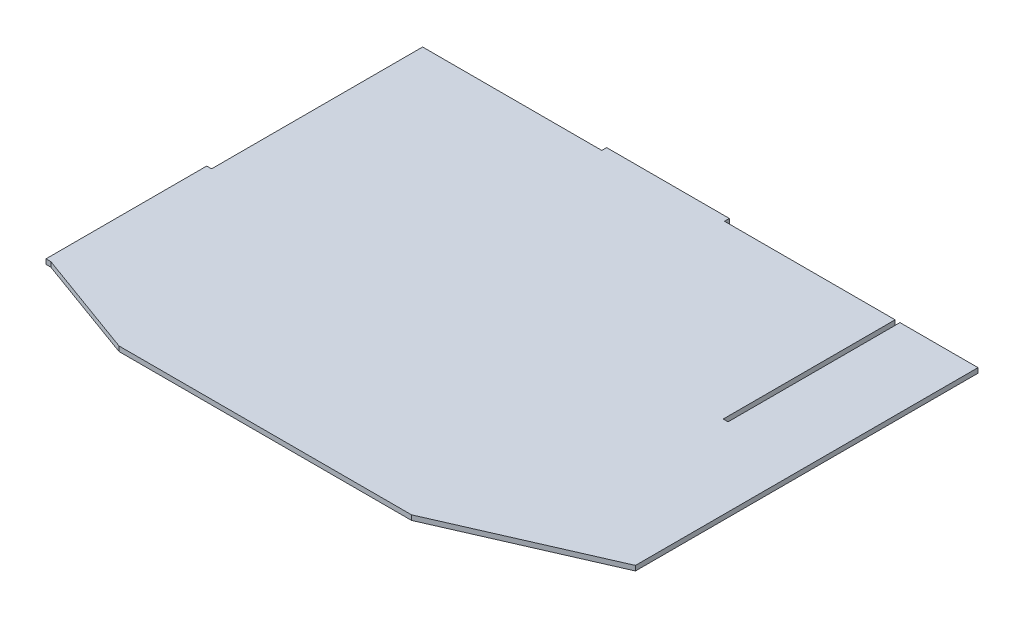
SolidWorks part; units mm, degrees
material "6061-T6 (SS)"
ref_plane "X-Y Datum" through (0, 0, 0) normal (0, 0, 1) x (1, 0, 0)
ref_plane "X-Z Datum" through (0, 0, 0) normal (0, 1, 0) x (1, 0, 0)
ref_plane "Y-Z Datum" through (0, 0, 0) normal (1, 0, 0) x (0, 0, -1)
sketch "Sketch1" plane through (0, 0, 0) normal (0, 0, 1) x (1, 0, 0)
  line L1 (-154.0561, -1.5875) -> (154.0561, -1.5875)
  line L2 (-154.0561, -1.5875) -> (-154.0561, 1.5875)
  line L3 (-154.0561, 1.5875) -> (154.0561, 1.5875)
  line L4 (154.0561, -1.5875) -> (154.0561, 1.5875)
  line L5 (-154.0561, -1.5875) -> (154.0561, 1.5875) construction
  line L6 (-154.0561, 1.5875) -> (154.0561, -1.5875) construction
  point P0 (0, 0)
  dimension "D1" = 3.175
  dimension "D2" = 308.1122
extrude "Boss-Extrude1" add sketch "Sketch1" along normal blind 267.83
sketch "Sketch3" plane through (154.0561, 0, 0) normal (1, 0, 0) x (0, 0, -1)
  line L0 (-267.83, 1.5875) -> (0, 1.5875) construction
  line L1 (-267.83, -1.5875) -> (-112.128, -1.5875)
  line L2 (-267.83, -1.5875) -> (-267.83, 1.5875)
  line L3 (-267.83, 1.5875) -> (-112.128, 1.5875)
  line L4 (-112.128, -1.5875) -> (-112.128, 1.5875)
  dimension "D1" = 155.702
extrude "Boss-Extrude3" add sketch "Sketch3" along normal blind 3.175
sketch "Sketch4" plane through (0, 0, 267.83) normal (0, 0, 1) x (1, 0, 0)
  line L1 (157.2311, -1.5875) -> (208.1047, -1.5875)
  line L2 (157.2311, -1.5875) -> (157.2311, 1.5875)
  line L3 (157.2311, 1.5875) -> (208.1047, 1.5875)
  line L4 (208.1047, -1.5875) -> (208.1047, 1.5875)
  dimension "D1" = 3.175
  dimension "D2" = 50.8737
extrude "Boss-Extrude4" add sketch "Sketch4" against normal blind 267.83
sketch "Sketch6" plane through (0, 1.5875, 0) normal (0, 1, 0) x (1, 0, 0)
  line L0 (106.5047, -267.83) -> (106.5047, -223.38)
  line L1 (208.1047, -267.83) -> (-154.0561, -267.83) construction
  line L2 (208.1047, -223.38) -> (106.5047, -223.38)
  line L3 (208.1047, 0) -> (208.1047, -267.83) construction
  line L4 (106.5047, -267.83) -> (208.1047, -223.38)
  line M9 (-154.0561, -267.83) -> (208.1047, -267.83)
  line M10 (208.1047, -267.83) -> (208.1047, 0)
  dimension "D1" = 44.45
  dimension "D2" = 101.6
extrude "Cut-Extrude1" cut sketch "Sketch6" against normal through all contours L4 M9 M10
sketch "Sketch8" plane through (0, 0, 0) normal (0, 0, -1) x (-1, 0, 0)
  line L1 (37.216, 1.5875) -> (-42.784, 1.5875)
  line L2 (37.216, 1.5875) -> (37.216, -1.5875)
  line L3 (37.216, -1.5875) -> (-42.784, -1.5875)
  line L4 (-42.784, 1.5875) -> (-42.784, -1.5875)
extrude "Boss-Extrude6" add sketch "Sketch8" along normal blind 3.175
sketch "Sketch11" plane through (0, -1.5875, 0) normal (0, -1, 0) x (1, 0, 0)
  line L0 (-84.2061, 267.83) -> (-84.2061, 242.43)
  line L1 (-154.0561, 267.83) -> (106.5047, 267.83) construction
  line L2 (-154.0561, 242.43) -> (-84.2061, 242.43)
  line L3 (-154.0561, 267.83) -> (-154.0561, 0) construction
  line L4 (-154.0561, 242.43) -> (-84.2061, 267.83)
  line M4 (-154.0561, 267.83) -> (-154.0561, 0)
  line M18 (106.5047, 267.83) -> (-154.0561, 267.83)
  dimension "D1" = 69.85
  dimension "D2" = 25.4
extrude "Cut-Extrude3" cut sketch "Sketch11" against normal through all contours L4 M4 M18
sketch "Sketch13" plane through (-154.0561, 0, 0) normal (-1, 0, 0) x (0, 0, 1)
  line L1 (137.65, -1.598) -> (242.43, -1.598)
  line L2 (137.65, -1.598) -> (137.65, 1.5875)
  line L3 (137.65, 1.5875) -> (242.43, 1.5875)
  line L4 (242.43, -1.598) -> (242.43, 1.5875)
extrude "Boss-Extrude7" add sketch "Sketch13" along normal blind 3.175
